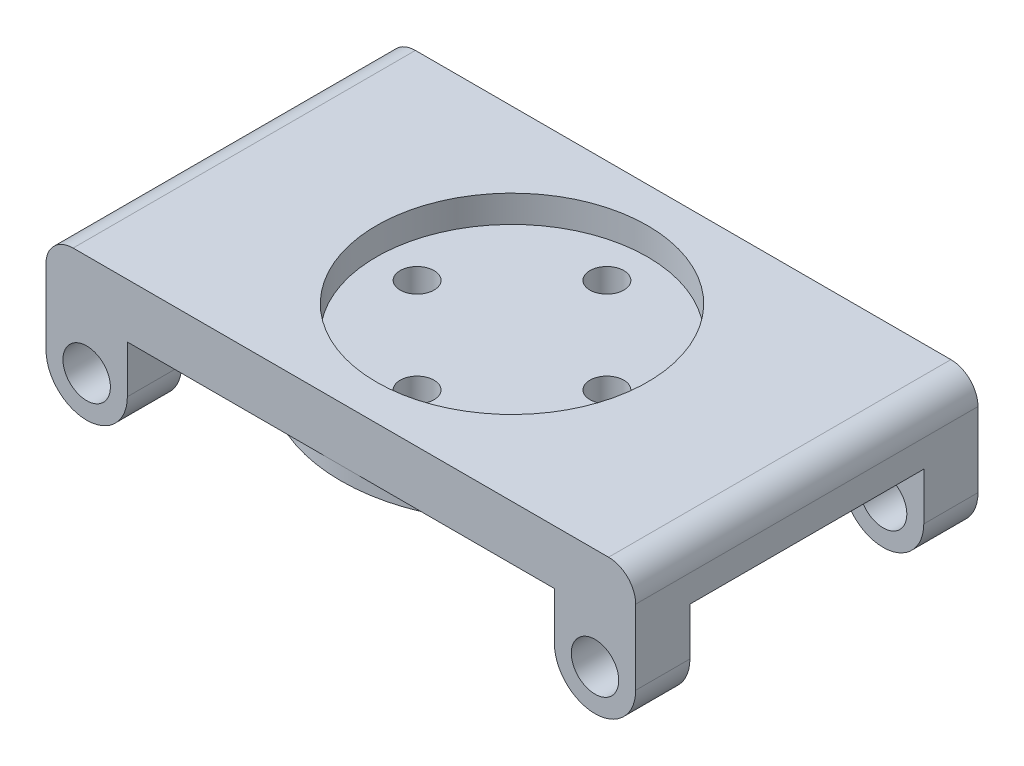
SolidWorks part; units mm, degrees
material "Esun Hard Tough Resin"
ref_plane "Front Plane" through (0, 0, 0) normal (0, 0, 1) x (1, 0, 0)
ref_plane "Top Plane" through (0, 0, 0) normal (0, 1, 0) x (1, 0, 0)
ref_plane "Right Plane" through (0, 0, 0) normal (1, 0, 0) x (0, 0, -1)
sketch "Sketch1" plane through (0, 0, 0) normal (0, 1, 0) x (1, 0, 0)
  line L1 (-21.75, -12.625) -> (21.75, -12.625)
  line L2 (-21.75, -12.625) -> (-21.75, 12.625)
  line L3 (-21.75, 12.625) -> (21.75, 12.625)
  line L4 (21.75, -12.625) -> (21.75, 12.625)
  line L5 (-21.75, -12.625) -> (21.75, 12.625) construction
  line L6 (-21.75, 12.625) -> (21.75, -12.625) construction
  point P0 (0, 0)
  dimension "D1" = 43.5
  dimension "D2" = 25.25
extrude "Boss-Extrude1" add sketch "Sketch1" along normal blind 4
sketch "Sketch5" plane through (0, 4, 0) normal (0, 1, 0) x (1, 0, 0)
  circle A0 centre (0, 0) radius 10
  dimension "D1" = 20
extrude "Cut-Extrude3" cut sketch "Sketch5" against normal blind 2
sketch "Sketch6" plane through (0, 0, 0) normal (0, -1, 0) x (1, 0, 0)
  line L0 (-21.75, 12.625) -> (21.75, 12.625) construction
  line L1 (21.75, -12.625) -> (-21.75, -12.625) construction
  circle A3 centre (0, 0) radius 12.625
extrude "Boss-Extrude3" add sketch "Sketch6" along normal blind 1
sketch "Sketch2" plane through (0, 4, 0) normal (0, 1, 0) x (1, 0, 0)
  circle A3 centre (0, 0) radius 7 construction
  circle A4 centre (0, 7) radius 1.25
  circle A5 centre (7, 0) radius 1.25
  circle A6 centre (0, -7) radius 1.25
  circle A7 centre (-7, 0) radius 1.25
  point P15 (0, 0)
  dimension "D1" = 2.5
  dimension "D2" = 14
  dimension "D3" = 4
extrude "Cut-Extrude4" cut sketch "Sketch2" against normal through all
sketch "Sketch4" plane through (0, 0, 12.625) normal (0, 0, 1) x (1, 0, 0)
  line L1 (-21.75, 0) -> (-15.75, 0)
  line L2 (-21.75, 0) -> (-21.75, -3.5)
  line L5 (0, 0) -> (0, 4) construction
  line L6 (-21.75, 4) -> (21.75, 4) construction
  line L8 (21.75, 0) -> (21.75, -3.5)
  line L9 (21.75, 0) -> (15.75, 0)
  line L11 (-21.75, 0) -> (0, 0)
  line L12 (15.75, 0) -> (21.75, 0)
  line L13 (-15.75, -3.5) -> (-15.75, 0)
  line L14 (15.75, -3.5) -> (15.75, 0)
  arc A0 (-21.75, -3.5) -> (-15.75, -3.5) centre (-18.75, -3.5) ccw
  circle A1 centre (-18.75, -3.5) radius 1.75
  circle A2 centre (18.75, -3.5) radius 1.75
  arc A3 (21.75, -3.5) -> (15.75, -3.5) centre (18.75, -3.5) cw
  dimension "D2" = 3
  dimension "D4" = 3.5
  dimension "D5" = 3.5
extrude "Boss-Extrude2" add sketch "Sketch4" against normal blind 4
mirror "Mirror1" about plane through (0, 0, 0) normal (0, 0, 1) of "Boss-Extrude2"
fillet "Fillet1" radius 2 2 edges at (21.75, 4, 0) (-21.75, 4, 0)
